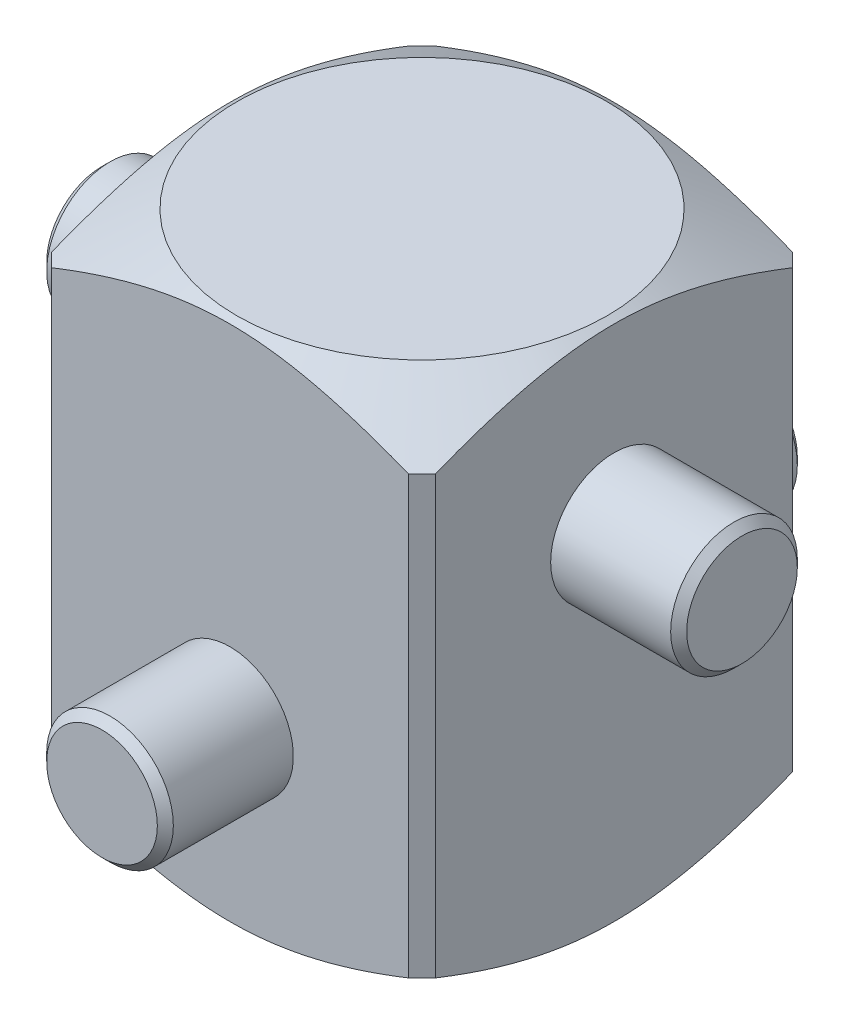
SolidWorks part; units mm, degrees
material "Plain Carbon Steel"
ref_plane "Front Plane" through (0, 0, 0) normal (0, 0, 1) x (1, 0, 0)
ref_plane "Top Plane" through (0, 0, 0) normal (0, 1, 0) x (1, 0, 0)
ref_plane "Right Plane" through (0, 0, 0) normal (1, 0, 0) x (0, 0, -1)
sketch "Sketch1" plane through (0, 0, 0) normal (0, 1, 0) x (1, 0, 0)
  line L1 (-7.2, 7.2) -> (7.2, 7.2)
  line L2 (-7.2, 7.2) -> (-7.2, -7.2)
  line L3 (-7.2, -7.2) -> (7.2, -7.2)
  line L4 (7.2, 7.2) -> (7.2, -7.2)
  line L5 (-7.2, 7.2) -> (7.2, -7.2) construction
  line L6 (-7.2, -7.2) -> (7.2, 7.2) construction
  point P0 (0, 0)
  dimension "D1" = 14.4
extrude "Boss-Extrude1" add sketch "Sketch1" along normal blind 19.7
ref_axis "Axis1" through (0, 20.685, 0) along (0, -1, 0)
sketch "Sketch2" plane through (0, 0, 0) normal (0, 0, 1) x (1, 0, 0)
  line L0 (-6.95, 19.7) -> (-16.09, 19.7)
  line L1 (-7.2, 19.7) -> (7.2, 19.7) construction
  line L2 (-16.09, 19.7) -> (-16.09, 0)
  line L3 (-16.09, 0) -> (-6.95, 0)
  line L4 (-7.2, 0) -> (7.2, 0) construction
  line L5 (-6.95, 19.7) -> (-13.55, 15.8895)
  line L6 (-13.55, 15.8895) -> (-13.55, 3.8105)
  line L7 (-13.55, 3.8105) -> (-6.95, 0)
  line L8 (-7.2, 19.7) -> (-7.2, 0) construction
  point P10 (-13.55, 9.85)
  point P13 (-7.2, 9.85)
  dimension "D1" = 0.25
  dimension "D2" = 6.35
  dimension "D3" = 2.54
  dimension "D4" = 30
  dimension "D5" = 30
revolve "Cut-Revolve1" cut sketch "Sketch2" angle 360 about axis through (0, 20.685, 0) along (0, -1, 0)
sketch "Sketch3" plane through (0, 0, 0) normal (0, 0, 1) x (1, 0, 0)
  line L0 (0, 20.685) -> (0, -0.985) construction
  circle A0 centre (0, 6.7) radius 2.375
  dimension "D1" = 4.75
  dimension "D2" = 6.7
extrude "Boss-Extrude2" add sketch "Sketch3" along normal mid plane 24
sketch "Sketch4" plane through (0, 0, 0) normal (1, 0, 0) x (0, 0, -1)
  line L0 (0, 20.685) -> (0, -0.985) construction
  line L1 (6.95, 19.7) -> (-6.95, 19.7) construction
  circle A0 centre (0, 13) radius 2.375
  dimension "D1" = 4.75
  dimension "D2" = 6.7
extrude "Boss-Extrude3" add sketch "Sketch4" along normal mid plane 24
chamfer "Chamfer1" distance 0.3 angle 45 4 edges at (2.375, 6.7, -12) (-12, 13, -2.375) (12, 13, -2.375) (2.375, 6.7, 12)
chamfer "Chamfer2" distance 0.5 angle 45 4 edges at (7.2, 9.85, 7.2) (7.2, 9.85, -7.2) (-7.2, 9.85, 7.2) (-7.2, 9.85, -7.2)
